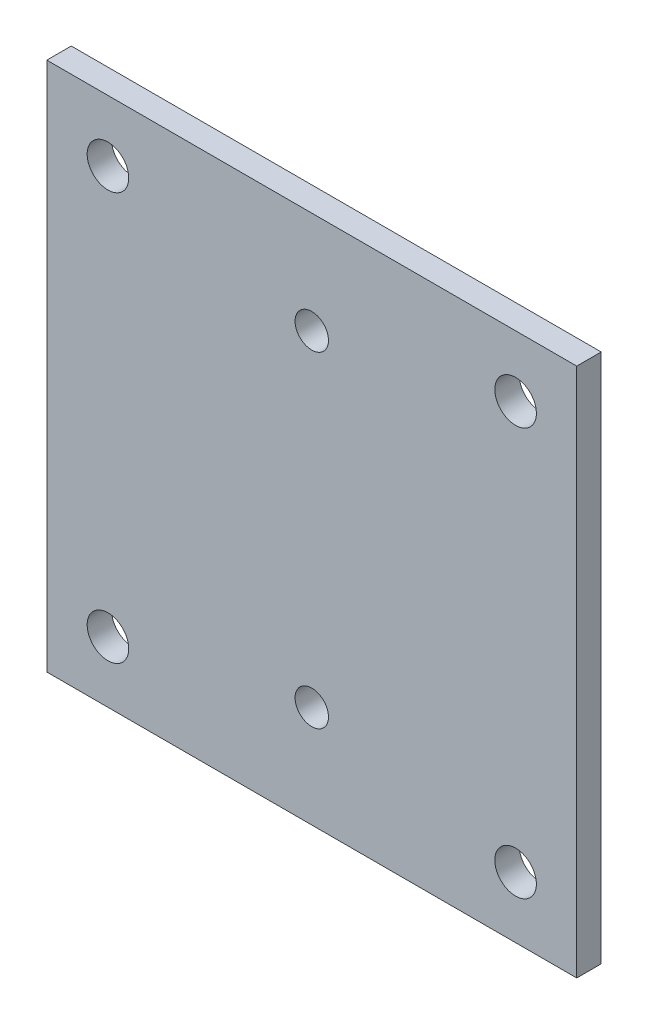
SolidWorks part; units mm, degrees
ref_plane "Front Plane" through (0, 0, 0) normal (0, 0, 1) x (1, 0, 0)
ref_plane "Top Plane" through (0, 0, 0) normal (0, 1, 0) x (1, 0, 0)
ref_plane "Right Plane" through (0, 0, 0) normal (1, 0, 0) x (0, 0, -1)
sketch "Sketch1" plane through (0, 0, 0) normal (0, 0, 1) x (1, 0, 0)
  line L0 (-32.5, 32.5) -> (32.5, 32.5)
  line L1 (-32.5, 32.5) -> (-32.5, -32.5)
  line L2 (-32.5, -32.5) -> (32.5, -32.5)
  line L3 (32.5, 32.5) -> (32.5, -32.5)
  line L4 (-32.5, 32.5) -> (32.5, -32.5) construction
  line L5 (-32.5, -32.5) -> (32.5, 32.5) construction
  circle A0 centre (-25, 25) radius 2.55
  circle A1 centre (25, 25) radius 2.55
  circle A2 centre (-25, -25) radius 2.55
  circle A3 centre (25, -25) radius 2.55
  circle A4 centre (0, 20) radius 2.05
  circle A5 centre (0, -20) radius 2.05
  point P0 (0, 0)
  point P15 (0, 0)
  point P20 (0, 32.5)
  dimension "D1" = 5.1
  dimension "D9" = 4.1
  dimension "D10" = 40
  dimension "D2" = 50
  dimension "D3" = 65
  dimension "D4" = 7.5
  dimension "D5" = 7.5
  dimension "D6" = 7.5
  dimension "D7" = 7.5
  dimension "D8" = 50
  dimension "D11" = 12.5
extrude "Boss-Extrude1" add sketch "Sketch1" along normal blind 3
